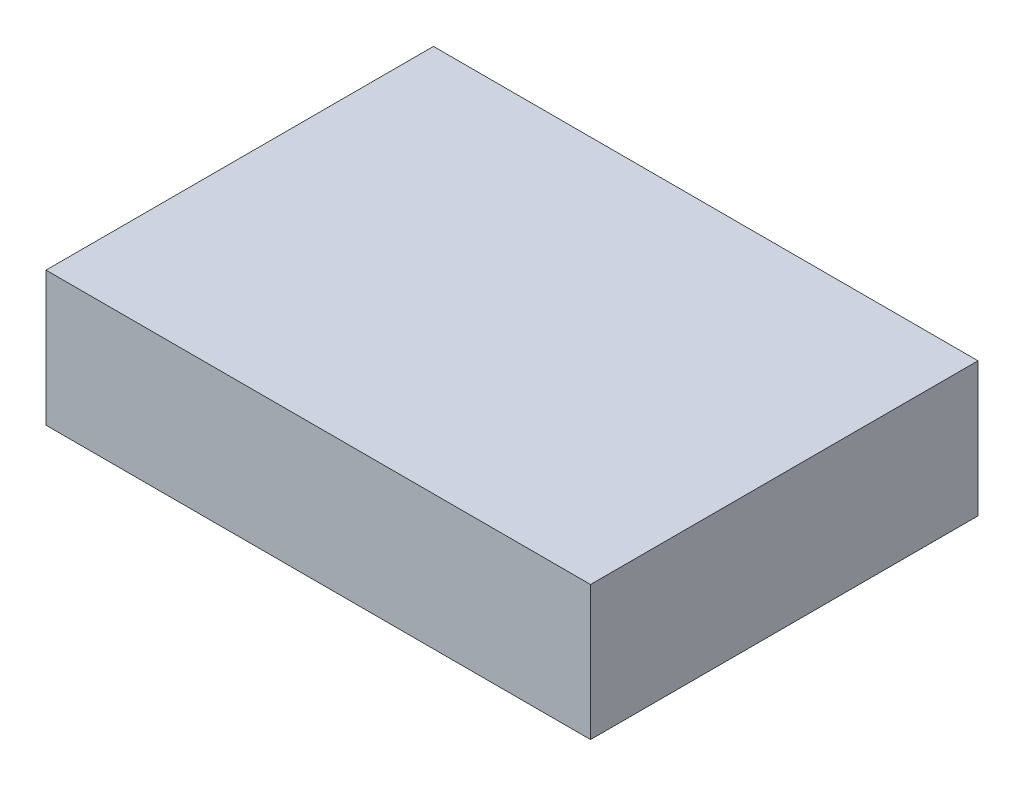
SolidWorks part; units mm, degrees
ref_plane "Plan de face" through (0, 0, 0) normal (0, 0, 1) x (1, 0, 0)
ref_plane "Plan de dessus" through (0, 0, 0) normal (0, 1, 0) x (1, 0, 0)
ref_plane "Plan de droite" through (0, 0, 0) normal (1, 0, 0) x (0, 0, -1)
sketch "Esquisse1" plane through (0, 0, 0) normal (0, 1, 0) x (1, 0, 0)
  line L1 (-26.35, -18.75) -> (26.35, -18.75)
  line L2 (-26.35, -18.75) -> (-26.35, 18.75)
  line L3 (-26.35, 18.75) -> (26.35, 18.75)
  line L4 (26.35, -18.75) -> (26.35, 18.75)
  line L5 (-26.35, -18.75) -> (26.35, 18.75) construction
  line L6 (-26.35, 18.75) -> (26.35, -18.75) construction
  point P0 (0, 0)
  dimension "D1" = 52.7
  dimension "D2" = 37.5
extrude "Boss.-Extru.1" add sketch "Esquisse1" along normal blind 13
